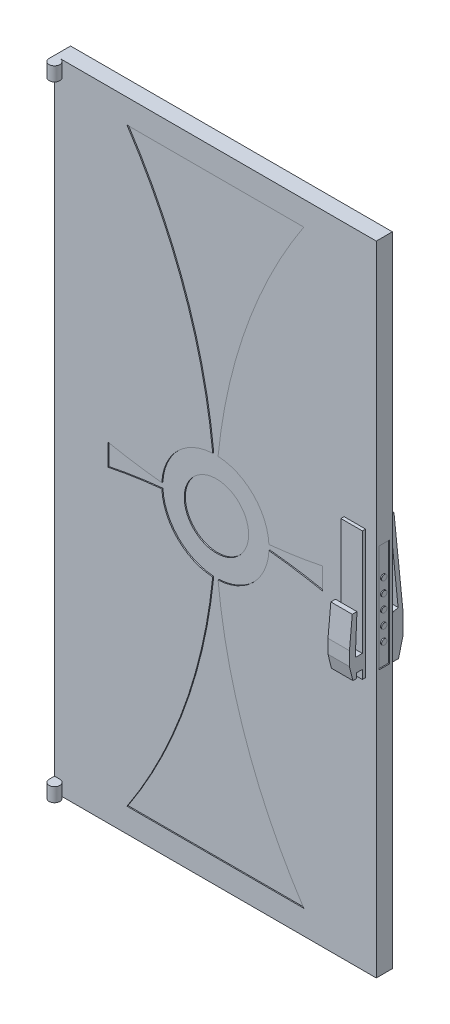
SolidWorks part; units mm, degrees
material "純金"
ref_plane "前基準面" through (0, 0, 0) normal (0, 0, 1) x (1, 0, 0)
ref_plane "上基準面" through (0, 0, 0) normal (0, 1, 0) x (1, 0, 0)
ref_plane "右基準面" through (0, 0, 0) normal (1, 0, 0) x (0, 0, -1)
sketch "草圖1" plane through (0, 0, 0) normal (0, 0, 1) x (1, 0, 0)
  line L1 (-15, 29.75) -> (15, 29.75)
  line L2 (-15, 29.75) -> (-15, -29.75)
  line L3 (-15, -29.75) -> (15, -29.75)
  line L4 (15, 29.75) -> (15, -29.75)
  line L5 (-15, 29.75) -> (15, -29.75) construction
  line L6 (-15, -29.75) -> (15, 29.75) construction
  point P0 (0, 0)
  dimension "D1" = 30
  dimension "D2" = 59.5
extrude "填料-伸長1" add sketch "草圖1" along normal blind 1.5
sketch "草圖2" plane through (0, 0, 1.5) normal (0, 0, 1) x (1, 0, 0)
  line L1 (-10, 27.5) -> (10, 27.5)
  line L2 (-10, 27.5) -> (-10, -27.5)
  line L3 (-10, -27.5) -> (10, -27.5)
  line L4 (10, 27.5) -> (10, -27.5)
  line L5 (-10, 27.5) -> (10, -27.5) construction
  line L6 (-10, -27.5) -> (10, 27.5) construction
  point P0 (0, 0)
  dimension "D1" = 20
  dimension "D2" = 55
extrude "除料-伸長1" cut sketch "草圖2" against normal blind 0.1
sketch "草圖3" plane through (0, 0, 1.4) normal (0, 0, 1) x (1, 0, 0)
  circle A0 centre (0, 0) radius 5
  dimension "D1" = 10
extrude "填料-伸長2" add sketch "草圖3" along normal blind 0.1
sketch "草圖4" plane through (0, 0, 1.4) normal (0, 0, 1) x (1, 0, 0)
  line L0 (-5, 0) -> (-49.6659, 0) construction
  line L1 (0, 5) -> (0, 51.1134) construction
  line L2 (8.2418, -27.5) -> (10, -27.5)
  line L3 (0, 27.5) -> (-10, 27.5)
  line L4 (-10, -1.0102) -> (-10, -27.5)
  line L5 (10, 1.0102) -> (10, 27.5)
  line L6 (10, -27.5) -> (10, 27.5)
  line L7 (10, 27.5) -> (-10, 27.5)
  line L8 (-10, 27.5) -> (-10, -27.5)
  line L9 (-10, -27.5) -> (10, -27.5)
  line L10 (10, -27.5) -> (10, -1.0102)
  line L11 (10, 27.5) -> (8.2418, 27.5)
  line L12 (-10, 27.5) -> (-10, 1.0102)
  line L13 (-10, -27.5) -> (-8.2418, -27.5)
  arc A0 (-8.2418, -27.5) -> (-0.25, -4.9937) centre (-50, 0) ccw
  arc A1 (-10, 1.0102) -> (-4.9937, 0.25) centre (0, 50) ccw
  arc A2 (8.2418, -27.5) -> (0.25, -4.9937) centre (50, 0) cw
  arc A3 (-10, -1.0102) -> (-4.9937, -0.25) centre (0, -50) cw
  circle A4 centre (0, 0) radius 5 construction
  circle A5 centre (0, 0) radius 5
  arc A6 (4.9937, -0.25) -> (10, -1.0102) centre (0, -50) cw
  arc A7 (4.9937, 0.25) -> (10, 1.0102) centre (0, 50) ccw
  arc A8 (-0.25, 4.9937) -> (-8.2418, 27.5) centre (-50, 0) ccw
  arc A9 (0.25, 4.9937) -> (8.2418, 27.5) centre (50, 0) cw
  circle M7 centre (0, 0) radius 5
  line M8 (10, -27.5) -> (10, 27.5)
  line M9 (10, 27.5) -> (-10, 27.5)
  line M10 (-10, 27.5) -> (-10, -27.5)
  line M11 (-10, -27.5) -> (10, -27.5)
  dimension "D1" = 100
  dimension "D2" = 100
  dimension "D3" = 0
extrude "填料-伸長3" add sketch "草圖4" along normal blind 0.1 contours A9 A7 M7 M8 M9 | A6 A5 A2 M11 M8 | A3 A0 M10 M11 M7 | A8 L3 A1 M7 M10
sketch "草圖5" plane through (0, 0, 1.5) normal (0, 0, 1) x (1, 0, 0)
  circle A0 centre (0, 0) radius 5
extrude "除料-伸長2" cut sketch "草圖5" against normal blind 0.1
sketch "草圖6" plane through (0, 0, 1.4) normal (0, 0, 1) x (1, 0, 0)
  circle A0 centre (0, 0) radius 3
  dimension "D1" = 6
extrude "除料-伸長3" cut sketch "草圖6" against normal blind 0.1
sketch "草圖7" plane through (0, 0, 0) normal (0, 0, -1) x (-1, 0, 0)
  line L4 (-8.2418, -27.5) -> (8.2418, -27.5)
  line L5 (-10, 1.0102) -> (-10, -1.0102)
  line L6 (8.2418, 27.5) -> (-8.2418, 27.5)
  line L7 (10, -1.0102) -> (10, 1.0102)
  line L8 (-8.2418, -27.5) -> (8.2418, -27.5)
  line L9 (-10, 1.0102) -> (-10, -1.0102)
  line L10 (8.2418, 27.5) -> (-8.2418, 27.5)
  line L11 (10, -1.0102) -> (10, 1.0102)
  arc A12 (10, -1.0102) -> (4.9937, -0.25) centre (0, -50) ccw
  arc A13 (0.25, -4.9937) -> (4.9937, -0.25) centre (0, 0) ccw
  arc A14 (0.25, -4.9937) -> (8.2418, -27.5) centre (50, 0) ccw
  arc A15 (-8.2418, -27.5) -> (-0.25, -4.9937) centre (-50, 0) ccw
  arc A16 (-4.9937, -0.25) -> (-0.25, -4.9937) centre (0, 0) ccw
  arc A17 (-4.9937, -0.25) -> (-10, -1.0102) centre (0, -50) ccw
  arc A18 (-10, 1.0102) -> (-4.9937, 0.25) centre (0, 50) ccw
  arc A19 (-0.25, 4.9937) -> (-4.9937, 0.25) centre (0, 0) ccw
  arc A20 (-0.25, 4.9937) -> (-8.2418, 27.5) centre (-50, 0) ccw
  arc A21 (8.2418, 27.5) -> (0.25, 4.9937) centre (50, 0) ccw
  arc A22 (4.9937, 0.25) -> (0.25, 4.9937) centre (0, 0) ccw
  arc A23 (4.9937, 0.25) -> (10, 1.0102) centre (0, 50) ccw
  arc A24 (10, -1.0102) -> (4.9937, -0.25) centre (0, -50) ccw
  arc A25 (0.25, -4.9937) -> (4.9937, -0.25) centre (0, 0) ccw
  arc A26 (0.25, -4.9937) -> (8.2418, -27.5) centre (50, 0) ccw
  arc A27 (-8.2418, -27.5) -> (-0.25, -4.9937) centre (-50, 0) ccw
  arc A28 (-4.9937, -0.25) -> (-0.25, -4.9937) centre (0, 0) ccw
  arc A29 (-4.9937, -0.25) -> (-10, -1.0102) centre (0, -50) ccw
  arc A30 (-10, 1.0102) -> (-4.9937, 0.25) centre (0, 50) ccw
  arc A31 (-0.25, 4.9937) -> (-4.9937, 0.25) centre (0, 0) ccw
  arc A32 (-0.25, 4.9937) -> (-8.2418, 27.5) centre (-50, 0) ccw
  arc A33 (8.2418, 27.5) -> (0.25, 4.9937) centre (50, 0) ccw
  arc A34 (4.9937, 0.25) -> (0.25, 4.9937) centre (0, 0) ccw
  arc A35 (4.9937, 0.25) -> (10, 1.0102) centre (0, 50) ccw
  dimension "D1" = 0
extrude "除料-伸長4" cut sketch "草圖7" against normal blind 0.1
sketch "草圖8" plane through (0, 0, 0.1) normal (0, 0, -1) x (-1, 0, 0)
  circle A0 centre (0, 0) radius 3 construction
  circle A1 centre (0, 0) radius 3
extrude "除料-伸長5" cut sketch "草圖8" against normal blind 0.1
sketch "草圖9" plane through (15, 0, 0) normal (1, 0, 0) x (0, 0, -1)
  line L0 (-0.75, 29.75) -> (-0.75, -29.75) construction
  line L1 (-1.5, 29.75) -> (0, 29.75) construction
  line L2 (-1.5, -29.75) -> (0, -29.75) construction
  line L3 (-0.75, -29.75) -> (0, 0) construction
  line L4 (0, 0) -> (-1.5, 0) construction
  line L5 (-1.5, -29.75) -> (-1.5, 29.75) construction
  line L7 (-1.25, 5) -> (-0.25, 5)
  line L8 (-1.25, 5) -> (-1.25, -5)
  line L9 (-1.25, -5) -> (-0.25, -5)
  line L10 (-0.25, 5) -> (-0.25, -5)
  line L11 (-1.25, 5) -> (-0.25, -5) construction
  line L12 (-1.25, -5) -> (-0.25, 5) construction
  point P11 (-0.75, 0)
  dimension "D1" = 10
  dimension "D2" = 1
extrude "除料-伸長6" cut sketch "草圖9" against normal blind 0.1
sketch "草圖10" plane through (14.9, 0, 0) normal (1, 0, 0) x (0, 0, -1)
  line L14 (-0.75, 5) -> (-0.75, -5) construction
  line L15 (-0.25, 5) -> (-1.25, 5) construction
  line L16 (-1.25, -5) -> (-0.25, -5) construction
  line L17 (-1.25, -5) -> (-0.25, -5) construction
  circle A0 centre (-0.75, -3) radius 0.25
  circle A1 centre (-0.75, -1.7) radius 0.25
  circle A2 centre (-0.75, -0.4) radius 0.25
  circle A3 centre (-0.75, 0.9) radius 0.25
  circle A4 centre (-0.75, 2.2) radius 0.25
  dimension "D1" = 0.5
  dimension "D2" = 2
  dimension "D3" = 5
extrude "填料-伸長4" add sketch "草圖10" along normal blind 0.1
sketch "草圖11" plane through (0, 0, 1.5) normal (0, 0, 1) x (1, 0, 0)
  line L0 (13, 29.75) -> (13, -29.75) construction
  line L1 (15, 29.75) -> (-15, 29.75) construction
  line L2 (-15, -29.75) -> (15, -29.75) construction
  line L3 (15, -29.75) -> (15, 29.75) construction
  line L5 (12, 6) -> (14, 6)
  line L6 (12, 6) -> (12, -6)
  line L7 (12, -6) -> (14, -6)
  line L8 (14, 6) -> (14, -6)
  line L9 (12, 6) -> (14, -6) construction
  line L10 (12, -6) -> (14, 6) construction
  point P8 (13, 0)
  dimension "D1" = 2
  dimension "D2" = 2
  dimension "D3" = 12
extrude "填料-伸長5" add sketch "草圖11" along normal blind 1.5
sketch "草圖12" plane through (14, 0, 0) normal (1, 0, 0) x (0, 0, -1)
  line L0 (-1.8, 6) -> (-1.8, -3.8928)
  line L1 (-3, 6) -> (-1.5, 6) construction
  line L2 (-1.8, 6) -> (-3, 6)
  line L3 (-3, 6) -> (-3, -3.0734)
  line L4 (-3, -6) -> (-3, 6) construction
  line L5 (-3, -6) -> (-1.8, -6)
  line L6 (-3, -6) -> (-1.5, -6) construction
  line L7 (-1.5, -29.75) -> (-1.5, 29.75) construction
  line L8 (-1.8, -6) -> (-1.8, -5.1883)
  line L9 (-1.8, -5.1883) -> (-2.363, -5.1883)
  line L10 (-1.8, -3.8928) -> (-2.456, -3.8928)
  line L11 (-3, -6) -> (-3, -4.3568)
  line L12 (-3, -4.3568) -> (-2.6783, -5.6509)
  line L13 (-2.6783, -5.6509) -> (-2.363, -5.6509)
  line L14 (-2.363, -5.6509) -> (-2.363, -5.1883)
  line L15 (-3, -3.0734) -> (-2.7366, -0.2671)
  line L16 (-2.7366, -0.2671) -> (-2.3011, -0.2671)
  line L17 (-2.3011, -0.2671) -> (-2.456, -3.8928)
  dimension "D1" = 0.3
  dimension "D2" = 0.3
extrude "除料-伸長7" cut sketch "草圖12" against normal through all
sketch "草圖13" plane through (0, 0, 0) normal (0, 0, -1) x (-1, 0, 0)
  line L0 (-14, -6) -> (-14, 6) construction
  line L1 (-12, -6) -> (-14, -6) construction
  line L2 (-12, 6) -> (-12, -6) construction
  line L3 (-14, 6) -> (-12, 6) construction
  line L4 (-14, -6) -> (-14, 6)
  line L5 (-12, -6) -> (-14, -6)
  line L6 (-12, 6) -> (-12, -6)
  line L7 (-14, 6) -> (-12, 6)
extrude "填料-伸長6" add sketch "草圖13" along normal blind 2
sketch "草圖14" plane through (14, 0, 0) normal (1, 0, 0) x (0, 0, -1)
  line L0 (1.1529, 6) -> (2, -2.4774)
  line L1 (2, 6) -> (0, 6) construction
  line L2 (2, 6) -> (2, -6) construction
  line L3 (1.1529, 6) -> (2, 6)
  line L4 (2, -4.3224) -> (1.5765, -6)
  line L5 (2, -6) -> (0, -6) construction
  line L6 (2, 6) -> (2, -2.4774)
  line L7 (2, -4.3224) -> (2, -6)
  line L8 (2, -6) -> (1.5765, -6)
extrude "除料-伸長8" cut sketch "草圖14" against normal through all
sketch "草圖15" plane through (14, 0, 0) normal (1, 0, 0) x (0, 0, -1)
  line L0 (0.7534, 6) -> (1.5379, -1.8516)
  line L1 (1.1529, 6) -> (0, 6) construction
  line L2 (0.7534, 6) -> (0, 6)
  line L3 (0, 6) -> (0, 3.7724)
  line L5 (0, 6) -> (0, -6) construction
  line L6 (0, 3.7724) -> (0.5709, 3.7724)
  line L7 (0.5709, 3.7724) -> (1.1457, -1.9798)
  line L8 (1.1457, -1.9798) -> (1.5379, -1.8516)
extrude "除料-伸長9" cut sketch "草圖15" against normal through all
sketch "草圖17" plane through (14, 0, 0) normal (1, 0, 0) x (0, 0, -1)
  line L0 (0.5709, 3.7724) -> (0.5709, -1.9862)
  line L1 (0.5709, -1.9862) -> (1.1457, -1.9798)
  line L2 (1.1457, -1.9798) -> (0.5709, 3.7724)
extrude "除料-伸長10" cut sketch "草圖17" against normal through all
sketch "草圖18" plane through (0, 29.75, 0) normal (0, 1, 0) x (1, 0, 0)
  line L0 (-15, -1.5) -> (-15, -2)
  line L1 (-15, -1.5) -> (-15, 0) construction
  line L2 (15, -1.5) -> (-15, -1.5) construction
  circle A0 centre (-14.5, -2) radius 0.5
  line M4 (-15, -1.5) -> (15, -1.5)
  dimension "D1" = 1
extrude "填料-伸長7" add sketch "草圖18" against normal through all contours A0 | A0 L0 M4
sketch "草圖19" plane through (-15, 0, 0) normal (-1, 0, 0) x (0, 0, 1)
  line L1 (1.5, 28.45) -> (2.5, 28.45)
  line L2 (1.5, 28.45) -> (1.5, -28.45)
  line L3 (1.5, -28.45) -> (2.5, -28.45)
  line L4 (2.5, 28.45) -> (2.5, -28.45)
  line L5 (2.5, -29.75) -> (2.5, 29.75) construction
  line L6 (2.5, 29.75) -> (1.5, 29.75) construction
  line L7 (1.5, -29.75) -> (2.5, -29.75) construction
  dimension "D1" = 1.3
  dimension "D2" = 1.3
extrude "除料-伸長11" cut sketch "草圖19" against normal blind 2
